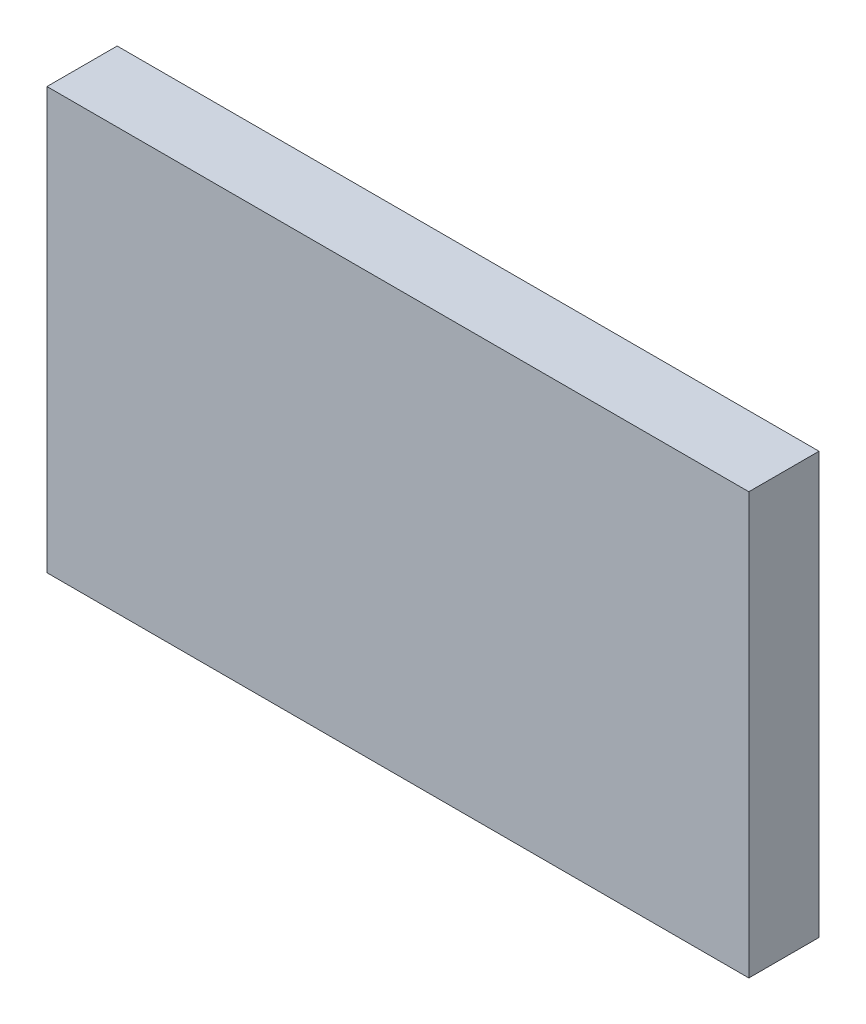
SolidWorks part; units mm, degrees
ref_plane "前视基准面" through (0, 0, 0) normal (0, 0, 1) x (1, 0, 0)
ref_plane "上视基准面" through (0, 0, 0) normal (0, 1, 0) x (1, 0, 0)
ref_plane "右视基准面" through (0, 0, 0) normal (1, 0, 0) x (0, 0, -1)
other "Configuration Table"
sketch "草图1" plane through (0, 0, 0) normal (0, 0, 1) x (1, 0, 0)
  line L1 (0, 0) -> (100000, 0)
  line L2 (0, 0) -> (0, 60000)
  line L3 (0, 60000) -> (100000, 60000)
  line L4 (100000, 0) -> (100000, 60000)
extrude "凸台-拉伸1" add sketch "草图1" against normal blind 10000
